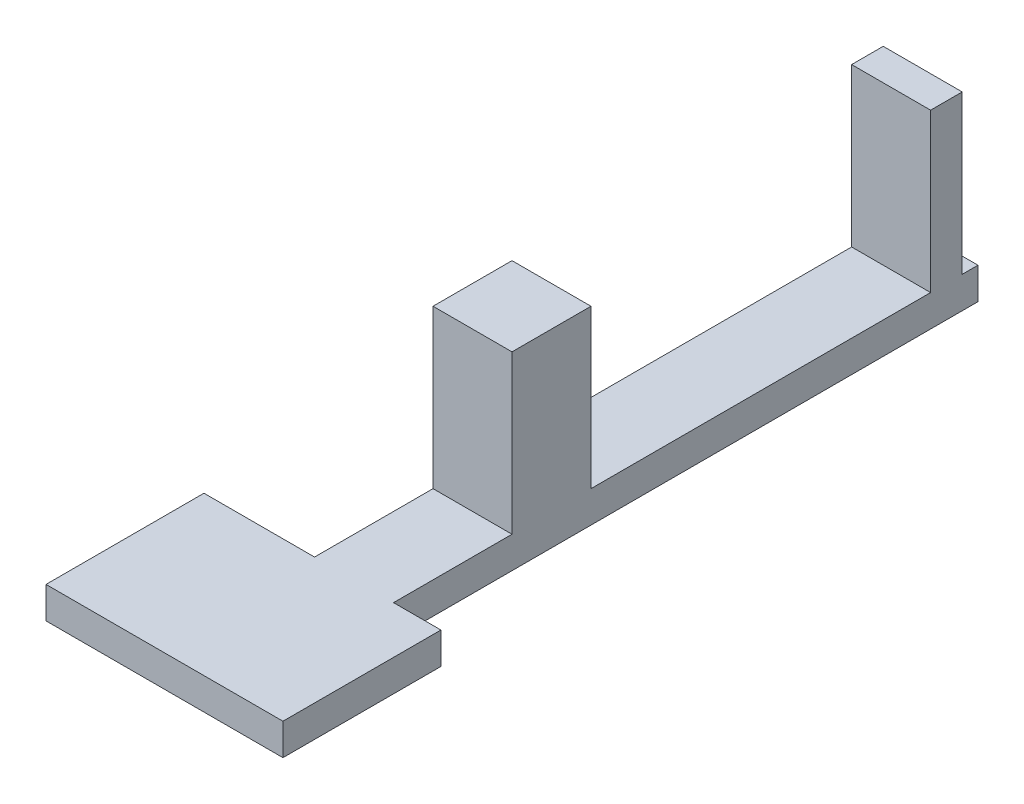
SolidWorks part; units mm, degrees
ref_plane "Front Plane" through (0, 0, 0) normal (0, 0, 1) x (1, 0, 0)
ref_plane "Top Plane" through (0, 0, 0) normal (0, 1, 0) x (1, 0, 0)
ref_plane "Right Plane" through (0, 0, 0) normal (1, 0, 0) x (0, 0, -1)
sketch "Sketch1" plane through (0, 0, 0) normal (0, 0, 1) x (1, 0, 0)
  line L1 (-25, 10) -> (25, 10)
  line L2 (-25, 10) -> (-25, -10)
  line L3 (-25, -10) -> (25, -10)
  line L4 (25, 10) -> (25, -10)
  line L5 (-25, 10) -> (25, -10) construction
  line L6 (-25, -10) -> (25, 10) construction
  point P0 (0, 0)
  dimension "D1" = 50
  dimension "D2" = 20
extrude "Boss-Extrude1" add sketch "Sketch1" along normal blind 470
sketch "Sketch2" plane through (0, 10, 0) normal (0, 1, 0) x (1, 0, 0)
  line L0 (25, -470) -> (-25, -470) construction
  line L1 (55, -370) -> (-95, -370)
  line L2 (55, -370) -> (55, -470)
  line L3 (55, -470) -> (-95, -470)
  line L4 (-95, -370) -> (-95, -470)
  line L5 (55, -370) -> (-95, -470) construction
  line L6 (55, -470) -> (-95, -370) construction
  line L13 (25, -470) -> (25, 0) construction
  point P0 (-20, -420)
  point P5 (0, 0)
  dimension "D1" = 100
  dimension "D2" = 150
  dimension "D3" = 30
extrude "Boss-Extrude2" add sketch "Sketch2" against normal blind 20
sketch "Sketch3" plane through (0, 10, 0) normal (0, 1, 0) x (1, 0, 0)
  line L7 (25, -370) -> (25, 0) construction
  line L12 (-25, -30) -> (25, -30)
  line L13 (-25, -30) -> (-25, -10)
  line L14 (-25, -10) -> (25, -10)
  line L15 (25, -30) -> (25, -10)
  line L16 (-25, -30) -> (25, -10) construction
  line L17 (-25, -10) -> (25, -30) construction
  line L18 (25, 0) -> (-25, 0) construction
  line L19 (-25, -295) -> (25, -295)
  line L20 (-25, -295) -> (-25, -245)
  line L21 (-25, -245) -> (25, -245)
  line L22 (25, -295) -> (25, -245)
  line L23 (-25, -295) -> (25, -245) construction
  line L24 (-25, -245) -> (25, -295) construction
  point P0 (0, -20)
  point P7 (0, -270)
  dimension "D1" = 10
  dimension "D2" = 20
  dimension "D3" = 50
  dimension "D4" = 250
  dimension "D5" = 50
  dimension "D6" = 50
extrude "Boss-Extrude3" add sketch "Sketch3" along normal blind 100
